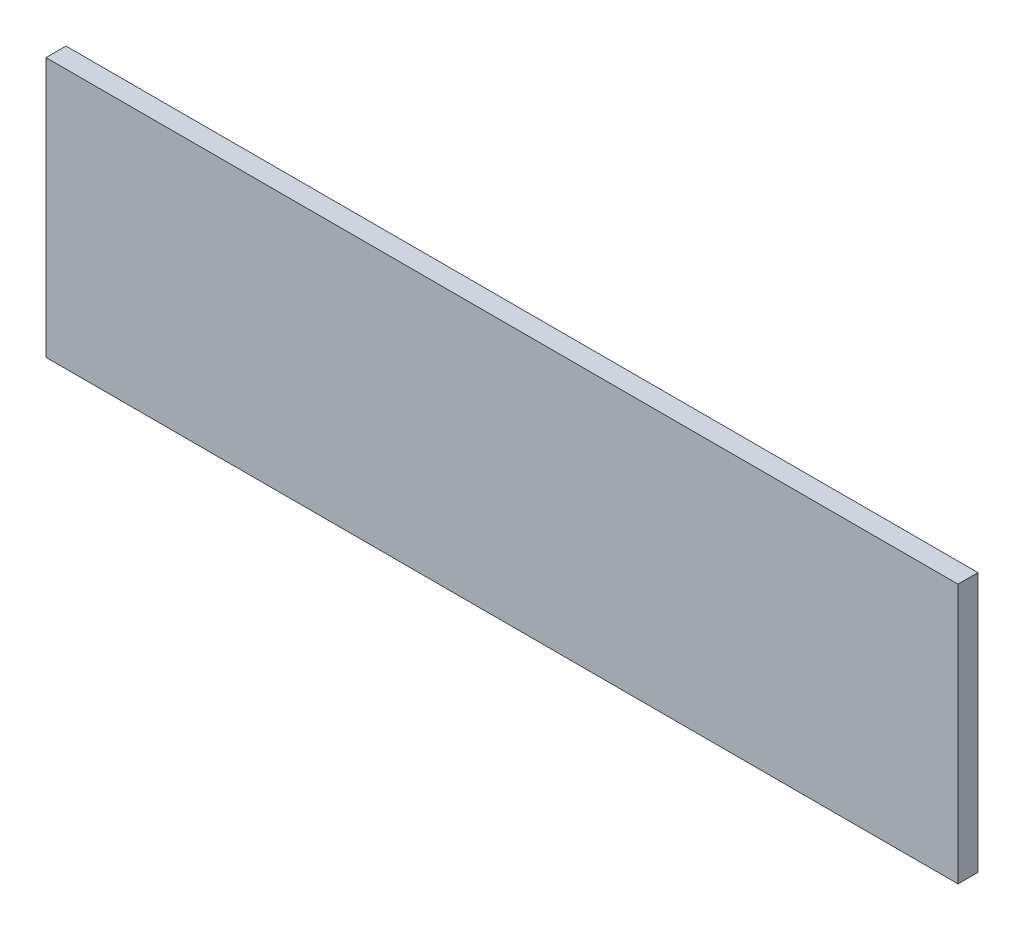
SolidWorks part; units mm, degrees
ref_plane "Front" through (0, 0, 0) normal (0, 0, 1) x (1, 0, 0)
ref_plane "Top" through (0, 0, 0) normal (0, 1, 0) x (1, 0, 0)
ref_plane "Right" through (0, 0, 0) normal (1, 0, 0) x (0, 0, -1)
sketch "Sketch1" plane through (0, 0, 0) normal (0, 0, 1) x (1, 0, 0)
  line L1 (-137, -39) -> (137, -39)
  line L2 (-137, -39) -> (-137, 39)
  line L3 (-137, 39) -> (137, 39)
  line L4 (137, -39) -> (137, 39)
  line L5 (-137, -39) -> (137, 39) construction
  line L6 (-137, 39) -> (137, -39) construction
  point P0 (0, 0)
  dimension "D1" = 78
  dimension "D2" = 274
extrude "Boss-Extrude1" add sketch "Sketch1" along normal blind 6
